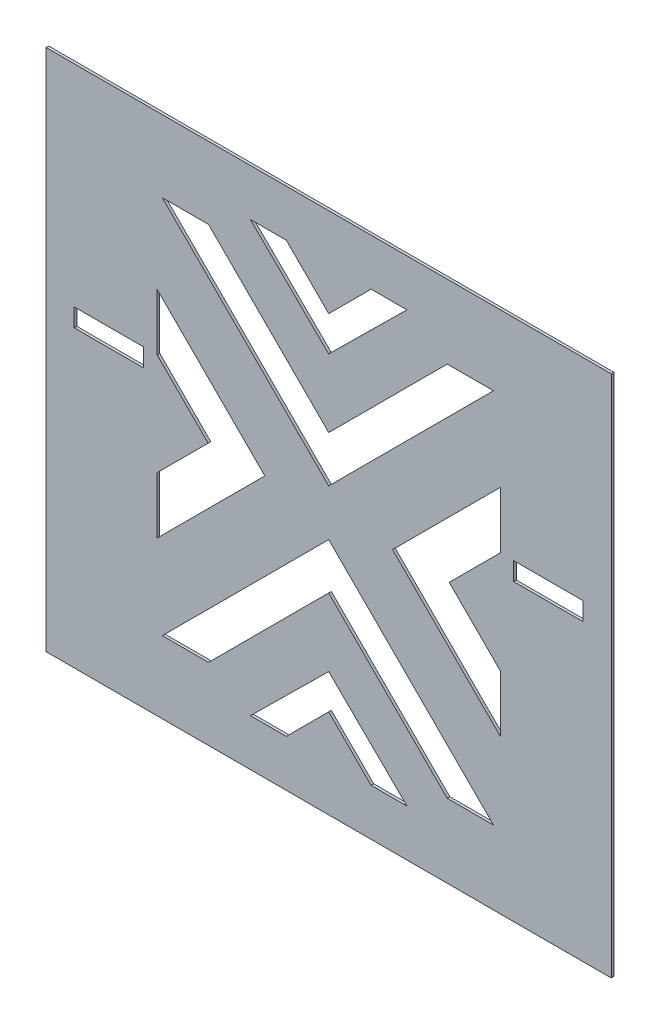
SolidWorks part; units mm, degrees
ref_plane "前视基准面" through (0, 0, 0) normal (0, 0, 1) x (1, 0, 0)
ref_plane "上视基准面" through (0, 0, 0) normal (0, 1, 0) x (1, 0, 0)
ref_plane "右视基准面" through (0, 0, 0) normal (1, 0, 0) x (0, 0, -1)
sketch "草图1" plane through (0, 0, 0) normal (0, 0, 1) x (1, 0, 0)
  line L1 (-108, 100) -> (108, 100)
  line L2 (-108, 100) -> (-108, -100)
  line L3 (-108, -100) -> (108, -100)
  line L4 (108, 100) -> (108, -100)
  line L5 (-108, 100) -> (108, -100) construction
  line L6 (-108, -100) -> (108, 100) construction
  point P0 (0, 0)
  dimension "D1" = 216
  dimension "D2" = 200
extrude "凸台-拉伸1" add sketch "草图1" along normal blind 1
sketch "草图2" plane through (0, 0, 1) normal (0, 0, 1) x (1, 0, 0)
  line L0 (0, 23.7223) -> (-46.7538, 70.4761) construction
  line L1 (0, 23.7223) -> (46.1438, 69.8661) construction
  line L2 (-46.7538, 70.4761) -> (-58.7538, 70.4761) construction
  line L3 (46.1438, 69.8661) -> (58.1438, 69.8661) construction
  line L4 (-1000, 0) -> (49000, 0) construction
  line L5 (0, -1000) -> (0, 49000) construction
  line L6 (-58.7538, 70.4761) -> (0, 11.7223) construction
  line L7 (0, 11.7223) -> (58.1438, 69.8661) construction
  line L8 (0, 55.3725) -> (25.0392, 80.1168) construction
  line L9 (-25.0392, 80.1168) -> (0, 55.3725) construction
  line L10 (-25.0392, 80.1168) -> (-17.0392, 80.1168) construction
  line L11 (-29.9084, 82.1168) -> (0, 52.5607)
  line L12 (-17.0392, 80.1168) -> (0, 63.0776) construction
  line L13 (0, 63.0776) -> (17.0392, 80.1168) construction
  line L14 (17.0392, 80.1168) -> (25.0392, 80.1168) construction
  line L15 (0, 26.5507) -> (-45.9253, 72.4761)
  line L16 (-45.9253, 72.4761) -> (-63.5822, 72.4761)
  line L17 (-63.5822, 72.4761) -> (0, 8.8939)
  line L18 (0, 8.8939) -> (62.9722, 71.8661)
  line L19 (45.3154, 71.8661) -> (62.9722, 71.8661)
  line L20 (0, 26.5507) -> (45.3154, 71.8661)
  line L21 (0, 20.8939) -> (-47.5822, 68.4761)
  line L22 (-47.5822, 68.4761) -> (-53.9253, 68.4761)
  line L23 (-53.9253, 68.4761) -> (0, 14.5507)
  line L24 (0, 14.5507) -> (53.3154, 67.8661)
  line L25 (46.9722, 67.8661) -> (53.3154, 67.8661)
  line L26 (0, 20.8939) -> (46.9722, 67.8661)
  line L27 (0, 52.5607) -> (29.9084, 82.1168)
  line L28 (16.2108, 82.1168) -> (29.9084, 82.1168)
  line L29 (0, 65.906) -> (16.2108, 82.1168)
  line L30 (-16.2108, 82.1168) -> (0, 65.906)
  line L31 (-29.9084, 82.1168) -> (-16.2108, 82.1168)
  line L32 (-20.17, 78.1168) -> (0, 58.1843)
  line L33 (0, 58.1843) -> (20.17, 78.1168)
  line L34 (17.8676, 78.1168) -> (20.17, 78.1168)
  line L35 (0, 60.2491) -> (17.8676, 78.1168)
  line L36 (-17.8676, 78.1168) -> (0, 60.2491)
  line L37 (-20.17, 78.1168) -> (-17.8676, 78.1168)
  dimension "D1" = 45
  dimension "D2" = 45
  dimension "D3" = 2
  dimension "D4" = 12
  dimension "D5" = 2
  dimension "D6" = 8
  dimension "D7" = 8
  dimension "D8" = 2
  dimension "D9" = 2
extrude "切除-拉伸2" cut sketch "草图2" against normal through all
mirror "镜向2" about plane through (0, 0, 0) normal (0, 1, 0) of "切除-拉伸2"
sketch "草图3" plane through (0, 0, 1) normal (0, 0, 1) x (1, 0, 0)
  line L0 (-63.5822, 36.3425) -> (-27.2397, 0) construction
  line L1 (-27.2397, 0) -> (-63.5822, -36.3425) construction
  line L2 (-63.5822, -36.3425) -> (-63.5822, -20.3425) construction
  line L3 (-63.5822, -20.3425) -> (-43.2397, 0) construction
  line L4 (-43.2397, 0) -> (-63.5822, 20.3425) construction
  line L5 (-63.5822, 20.3425) -> (-63.5822, 36.3425) construction
  line L6 (-1000, 0) -> (49000, 0) construction
  line L7 (-46.0681, 0) -> (-65.5822, 19.5141)
  line L8 (-65.5822, 19.5141) -> (-65.5822, 41.1709)
  line L9 (-65.5822, 41.1709) -> (-24.4113, 0)
  line L10 (-24.4113, 0) -> (-65.5822, -41.1709)
  line L11 (-65.5822, -41.1709) -> (-65.5822, -19.5141)
  line L12 (-65.5822, -19.5141) -> (-46.0681, 0)
  line L13 (-40.4113, 0) -> (-61.5822, 21.1709)
  line L14 (-61.5822, 21.1709) -> (-61.5822, 31.5141)
  line L15 (-61.5822, 31.5141) -> (-30.0681, 0)
  line L16 (-30.0681, 0) -> (-61.5822, -31.5141)
  line L17 (-61.5822, -31.5141) -> (-61.5822, -21.1709)
  line L18 (-61.5822, -21.1709) -> (-40.4113, 0)
  dimension "D1" = 16
  dimension "D2" = 16
  dimension "D3" = 0
  dimension "D4" = 2
  dimension "D5" = 2
extrude "切除-拉伸3" cut sketch "草图3" against normal through all
mirror "镜向3" about plane through (0, 0, 0) normal (1, 0, 0) of "切除-拉伸3"
sketch "草图4" plane through (0, 0, 1) normal (0, 0, 1) x (1, 0, 0)
  line L1 (-97.2542, 19.5141) -> (-70.705, 19.5141)
  line L2 (-97.2542, 19.5141) -> (-97.2542, 12.576)
  line L3 (-97.2542, 12.576) -> (-70.705, 12.576)
  line L4 (-70.705, 19.5141) -> (-70.705, 12.576)
extrude "切除-拉伸4" cut sketch "草图4" against normal through all
mirror "镜向4" about plane through (0, 0, 0) normal (1, 0, 0) of "切除-拉伸4"
